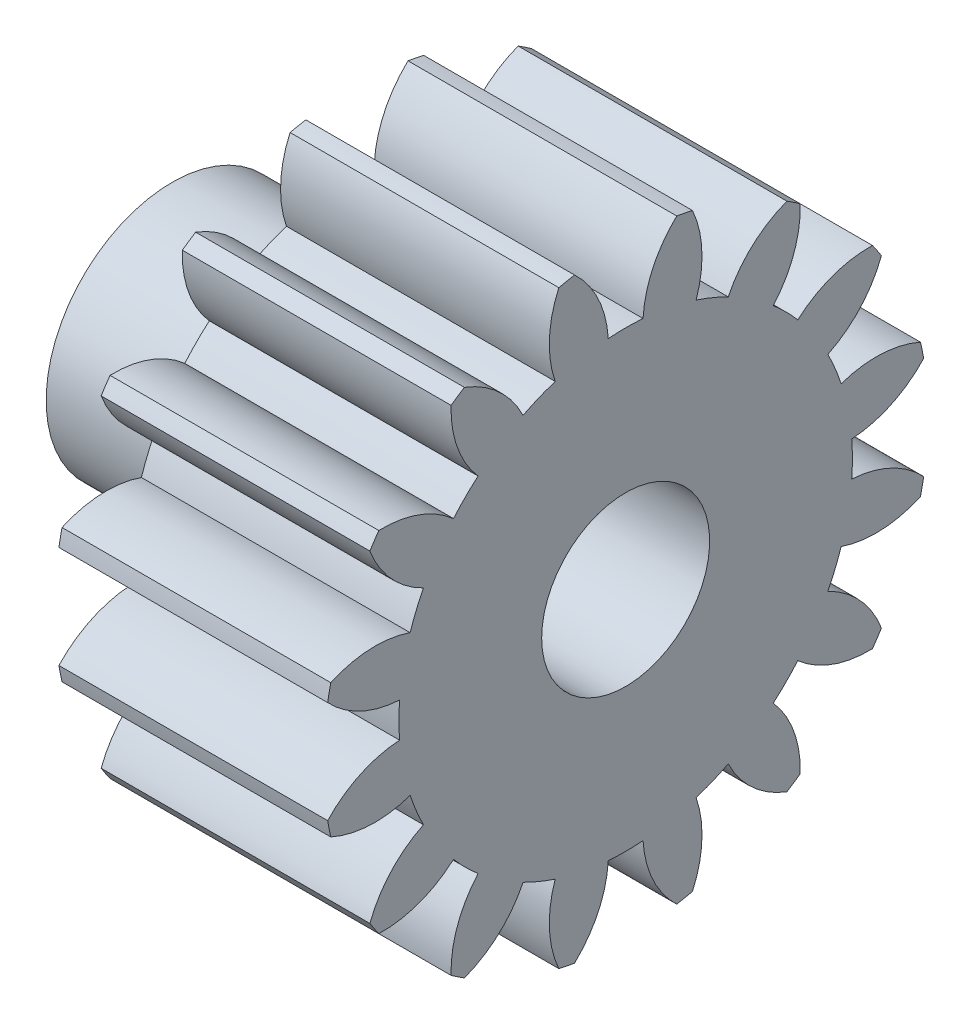
SolidWorks part; units mm, degrees
ref_plane "Plane1" through (0, 0, 0) normal (0, 0, 1) x (1, 0, 0)
ref_plane "Plane2" through (0, 0, 0) normal (0, 1, 0) x (1, 0, 0)
ref_plane "Plane3" through (0, 0, 0) normal (1, 0, 0) x (0, 0, -1)
other "Configuration Table"
sketch "HoldingSke" plane through (0, 0, 0) normal (0, 1, 0) x (1, 0, 0)
  line L0 (0, 0) -> (0.4806, -0.1378)
  line L1 (-15, 0) -> (100, 0) construction
  line L2 (0, 0) -> (-2.1039, 2.3779)
  line L3 (0, 0) -> (-11.863, 4.5341)
  line L4 (0, 0) -> (8.3015, 2.3804)
  line L5 (0, 0) -> (-35.6042, -13.2793)
  line L6 (0, 0) -> (-13.2634, -8.9489)
  line L7 (-2.1039, 2.3779) -> (6.0756, 39.4872)
  line L8 (-76.2, 54.61) -> (-74.4, 54.61)
  line L9 (-71.009, 38.7566) -> (-53.1078, 45.2721)
  line L10 (-76.2, 71.12) -> (104.1128, 71.12)
  line L11 (0, 0) -> (-16, 0)
  line L12 (-76.2, 101.6) -> (-76.133, 101.6)
  line L13 (24.9733, 27.94) -> (52.9518, 28.4284)
  line L14 (24.9733, 27.94) -> (24.9743, 27.94)
  line L15 (24.9733, 27.94) -> (100.4006, 29.5858)
  line L16 (-63.627, -2) -> (-12.827, -2)
  circle A0 centre (0, 0) radius 5
  circle A1 centre (0, 0) radius 7.5
  circle A2 centre (0, 0) radius 7.5
  circle A3 centre (0, 0) radius 5
  dimension "MHD" = 15
  dimension "Hub_dia" = 15
  dimension "Bore" = 10
  dimension "MBD" = 10
  dimension "Num_teeth" = 16
  dimension "Pitch" = 0.5
  dimension "Overall_len" = 38
  dimension "Show_teeth" = 16
  dimension "Thickness" = 16
  dimension "OAL" = 38.0001
  dimension "T_dim" = 1.8
  dimension "Ap" = 20
  dimension "H" = 19.05
  dimension "Pitch_radius" = 180.3128
  dimension "Width" = 16
  dimension "Backlash" = 0.067
  dimension "Addendum_fac" = 1
  dimension "Dedendum_fac" = 1.25
  dimension "Clearance_fac" = 0.25
  dimension "Dedendum_add" = 0.001
  dimension "Module" = 2
sketch "BasProSke" plane through (0, 0, 0) normal (0, 1, 0) x (1, 0, 0)
  line L0 (-10, 0) -> (60, 0) construction
  line L1 (0, 0) -> (0, 18)
  line L2 (0, 0) -> (16, 0)
  line L3 (16, 0) -> (16, 18)
  line L4 (16, 18) -> (0, 18)
  dimension "Thickness" = 16
  dimension "Diameter" = 36
revolve "Base-Revolve" add sketch "BasProSke" angle 360 about L0
sketch "TooCutSke" plane through (0, 0, 0) normal (1, 0, 0) x (0, 0, -1)
  line L1 (0, 0) -> (0, 107) construction
  line L2 (0, 0) -> (-1.6854, 15.911) construction
  line L3 (0, 0) -> (-6.2172, 31.2558) construction
  line L4 (-1.6854, 15.911) -> (-3.1086, 15.6279) construction
  arc A0 (1.0343, 13.4593) -> (-1.0343, 13.4593) centre (0, 0) ccw
  arc A1 (3.0657, 17.7628) -> (-3.0657, 17.7628) centre (0, 0) ccw
  circle A2 centre (0, 0) radius 16 construction
  circle A3 centre (0, 0) radius 15.0351 construction
  arc A4 (-1.0343, 13.4593) -> (-3.0657, 17.7628) centre (-7.4228, 13.075) ccw
  arc A5 (3.0657, 17.7628) -> (1.0343, 13.4593) centre (7.4228, 13.075) ccw
  dimension "Root_dia" = 26.998
  dimension "Overcut_dia" = 36.0508
  dimension "Pitch_dia" = 32
  dimension "Base_dia" = 30.0702
  dimension "Flank_rad" = 6.4
  dimension "Half_ang" = 11.25
  dimension "Half_CT" = 1.451
extrude "ToothCut" cut sketch "TooCutSke" along normal through all
fillet "Breaks" [suppressed] radius 0.04
fillet "RootFillets" [suppressed] radius 0.501
pattern_circular "TeethCuts" count 16 every 22.5 about axis through (-10, 0, 0) along (1, 0, 0) of "ToothCut", "RootFillets", "Breaks"
sketch "HubNeaOneSke" plane through (0, 0, 0) normal (-1, 0, 0) x (0, 0, 1)
  circle A0 centre (0, 0) radius 7.5
  dimension "Diameter" = 15
extrude "HubNearOne" add sketch "HubNeaOneSke" along normal blind 22.0001
sketch "HubNeaBotSke" plane through (0, 0, 0) normal (-1, 0, 0) x (0, 0, 1)
  circle A0 centre (0, 0) radius 7.5
  dimension "Diameter" = 15
extrude "HubNearBoth" [suppressed] add sketch "HubNeaBotSke" along normal blind 11
ref_plane "FarPln" through (16, 0, 0) normal (1, 0, 0) x (0, 0, -1)
sketch "HubFarSke" plane through (16, 0, 0) normal (1, 0, 0) x (0, 0, -1)
  circle A0 centre (0, 0) radius 7.5
  dimension "Diameter" = 15
extrude "HubFar" [suppressed] add sketch "HubFarSke" along normal blind 11
sketch "BorSke" plane through (0, 0, 0) normal (1, 0, 0) x (0, 0, -1)
  circle A0 centre (0, 0) radius 5
  dimension "Diameter" = 10
extrude "Bore" cut sketch "BorSke" along normal mid plane 76.0001
sketch "KeySke" plane through (0, 0, 0) normal (1, 0, 0) x (0, 0, -1)
  line L0 (-2, 0) -> (-2, 6.8)
  line L1 (-2, 6.8) -> (2, 6.8)
  line L2 (2, 6.8) -> (2, 0)
  line L3 (0, 0) -> (0, 34) construction
  line L4 (-2, 0) -> (2, 0)
  dimension "Offset" = 6.8
  dimension "Width" = 4
extrude "Keyway" [suppressed] cut sketch "KeySke" along normal mid plane 76.0001
pattern_circular "Keyway2" [suppressed] count 2 every 90 about axis through (-10, 0, 0) along (1, 0, 0)
sketch "Sketch1" plane through (-22.0001, 0, 0) normal (-1, 0, 0) x (0, 0, 1)
  circle A1 centre (0, 0) radius 7.5
  circle A2 centre (0, 0) radius 7.5
  dimension "D1" = 0
extrude "Cut-Extrude1" cut sketch "Sketch1" against normal blind 11
equation "' \"Module@HoldingSke\" = 6.35"
equation "' \"Num_teeth@HoldingSke\" = 12"
equation "' \"Ap@HoldingSke\" =  20"
equation "' \"Ap@HoldingSke\" = 20"
equation "' \"Width@HoldingSke\" = 0.5 * 25.4"
equation "' \"Hub_dia@HoldingSke\"= 1 * 25.4"
equation "' \"Hub_dia@HoldingSke\" = 1 * 25.4"
equation "' \"Overall_len@HoldingSke\" = 1.0 * 25.4"
equation "' \"Bore@HoldingSke\" = 0.75 * 25.4"
equation "' \"T_dim@HoldingSke\" = 0.1 * 25.4"
equation "' \"Width@KeySke\" = 0.25 * 25.4"
equation "' \"Show_teeth@HoldingSke\" = 13"
equation "' \"Backlash@HoldingSke\" = 0.009 * 25.4"
equation "' \"Addendum_fac@HoldingSke\" = 1.0"
equation "' \"Dedendum_fac@HoldingSke\" = 1.25"
equation "' \"Dedendum_add@HoldingSke\" = 0.00005 * 25.4"
equation "' \"Clearance_fac@HoldingSke\" = 0.25"
equation "\"Pitch@HoldingSke\" = 1 / \"Module@HoldingSke\""
equation "\"Overcut_dia@TooCutSke\" = (\"Num_teeth@HoldingSke\" + 2 * \"Addendum_fac@HoldingSke\") / \"Pitch@HoldingSke\" + 0.002 * 25.4"
equation "\"Pitch_dia@TooCutSke\" = \"Num_teeth@HoldingSke\" / \"Pitch@HoldingSke\""
equation "\"Base_dia@TooCutSke\" = \"Num_teeth@HoldingSke\" / \"Pitch@HoldingSke\" * cos((\"Ap@HoldingSke\"  * 3.14159265 / 180))"
equation "\"Root_dia@TooCutSke\" = (\"Num_teeth@HoldingSke\" + 2) / \"Pitch@HoldingSke\" - 2 * (\"Addendum_fac@HoldingSke\" + \"Dedendum_fac@HoldingSke\") / \"Pitch@HoldingSke\" - \"Dedendum_add@HoldingSke\" * 2"
equation "\"Half_ang@TooCutSke\" = 180 / \"Num_teeth@HoldingSke\""
equation "\"Half_CT@TooCutSke\" = \"Num_teeth@HoldingSke\" / \"Pitch@HoldingSke\" * sin((3.14159265 / 2 / \"Num_teeth@HoldingSke\")) / 2 - 7 * \"Backlash@HoldingSke\" / 4"
equation "\"Flank_rad@TooCutSke\" = \"Num_teeth@HoldingSke\" / \"Pitch@HoldingSke\" / 5"
equation "\"Radius@RootFillets\" = \"Clearance_fac@HoldingSke\" / \"Pitch@HoldingSke\" + \"Dedendum_add@HoldingSke\""
equation "\"Break_rad@Breaks\" = 0.02 / \"Pitch@HoldingSke\""
equation "\"Thickness@HoldingSke\" = \"Width@HoldingSke\""
equation "\"OAL@HoldingSke\" = \"Thickness@HoldingSke\""
equation "\"MHD@HoldingSke\" = (\"Num_teeth@HoldingSke\" + 2) / \"Pitch@HoldingSke\" - 2 * (\"Addendum_fac@HoldingSke\" + \"Dedendum_fac@HoldingSke\")  / \"Pitch@HoldingSke\" - \"Dedendum_add@HoldingSke\" * 2"
equation "\"MBD@HoldingSke\" = (\"Num_teeth@HoldingSke\" + 2) / \"Pitch@HoldingSke\" - 2 * (\"Addendum_fac@HoldingSke\" + \"Dedendum_fac@HoldingSke\")  / \"Pitch@HoldingSke\" - \"Dedendum_add@HoldingSke\" * 2 - 0.002 * 25.4"
equation "\"MHD@HoldingSke\" = ((sgn( \"MHD@HoldingSke\" - \"Hub_dia@HoldingSke\" )-1)*( \"MHD@HoldingSke\" - \"Hub_dia@HoldingSke\" ))/-2+ \"Hub_dia@HoldingSke\""
equation "\"MBD@HoldingSke\" = ((sgn( \"MBD@HoldingSke\" - \"Bore@HoldingSke\" )-1)*( \"MBD@HoldingSke\" - \"Bore@HoldingSke\" ))/-2+ \"Bore@HoldingSke\""
equation "\"OAL@HoldingSke\" = ((sgn( \"OAL@HoldingSke\" - \"Overall_len@HoldingSke\" )+1)*( \"OAL@HoldingSke\" - \"Overall_len@HoldingSke\" ))/2 + \"Overall_len@HoldingSke\" + 0.000002 * 25.4"
equation "\"Num_teeth@TeethCuts\" = int( \"Show_teeth@HoldingSke\" ) + 1"
equation "\"Num_teeth@TeethCuts\" = ((sgn( \"Num_teeth@TeethCuts\" - \"Num_teeth@HoldingSke\" )-1)*( \"Num_teeth@TeethCuts\" - \"Num_teeth@HoldingSke\" ))/-2+ \"Num_teeth@HoldingSke\""
equation "\"Num_teeth@TeethCuts\" = ((sgn( \"Num_teeth@TeethCuts\" - 2.0)+1)*( \"Num_teeth@TeethCuts\" - 2.0))/2 +2.0"
equation "\"Angle@TeethCuts\" = 360.0 / \"Num_teeth@HoldingSke\""
equation "\"Diameter@BasProSke\" = (\"Num_teeth@HoldingSke\" + 2 * \"Addendum_fac@HoldingSke\") / \"Pitch@HoldingSke\""
equation "\"Thickness@BasProSke\"  = \"Thickness@HoldingSke\""
equation "' \"Fillet_rad@BasProSke\" =  \"Thickness@HoldingSke\" * 0.05"
equation "' \"Fillet_rad@BasProSke\" = \"Thickness@HoldingSke\" * 0.05"
equation "\"MHD@HoldingSke\" = ((sgn( \"MHD@HoldingSke\" - \"Root_dia@TooCutSke\" )-1)*( \"MHD@HoldingSke\" - \"Root_dia@TooCutSke\" ))/-2+ \"Root_dia@TooCutSke\""
equation "\"Diameter@HubNeaOneSke\" = \"MHD@HoldingSke\""
equation "\"Length@HubNearOne\" = \"OAL@HoldingSke\" - \"Thickness@BasProSke\""
equation "\"Diameter@HubNeaBotSke\" = \"MHD@HoldingSke\""
equation "\"Length@HubNearBoth\" = ( \"OAL@HoldingSke\" - \"Thickness@BasProSke\" ) / 2.0"
equation "\"Thickness@FarPln\" = \"Thickness@BasProSke\""
equation "\"Diameter@HubFarSke\" = \"MHD@HoldingSke\""
equation "\"Length@HubFar\" = ( \"OAL@HoldingSke\" - \"Thickness@BasProSke\" ) / 2.0"
equation "\"Diameter@BorSke\" = \"MBD@HoldingSke\""
equation "\"D1@Bore\" = \"OAL@HoldingSke\" * 2.0"
equation "\"D1@Keyway\" = \"OAL@HoldingSke\" * 2.0"
equation "\"Offset@KeySke\" = \"T_dim@HoldingSke\" + \"MBD@HoldingSke\" / 2.0"
